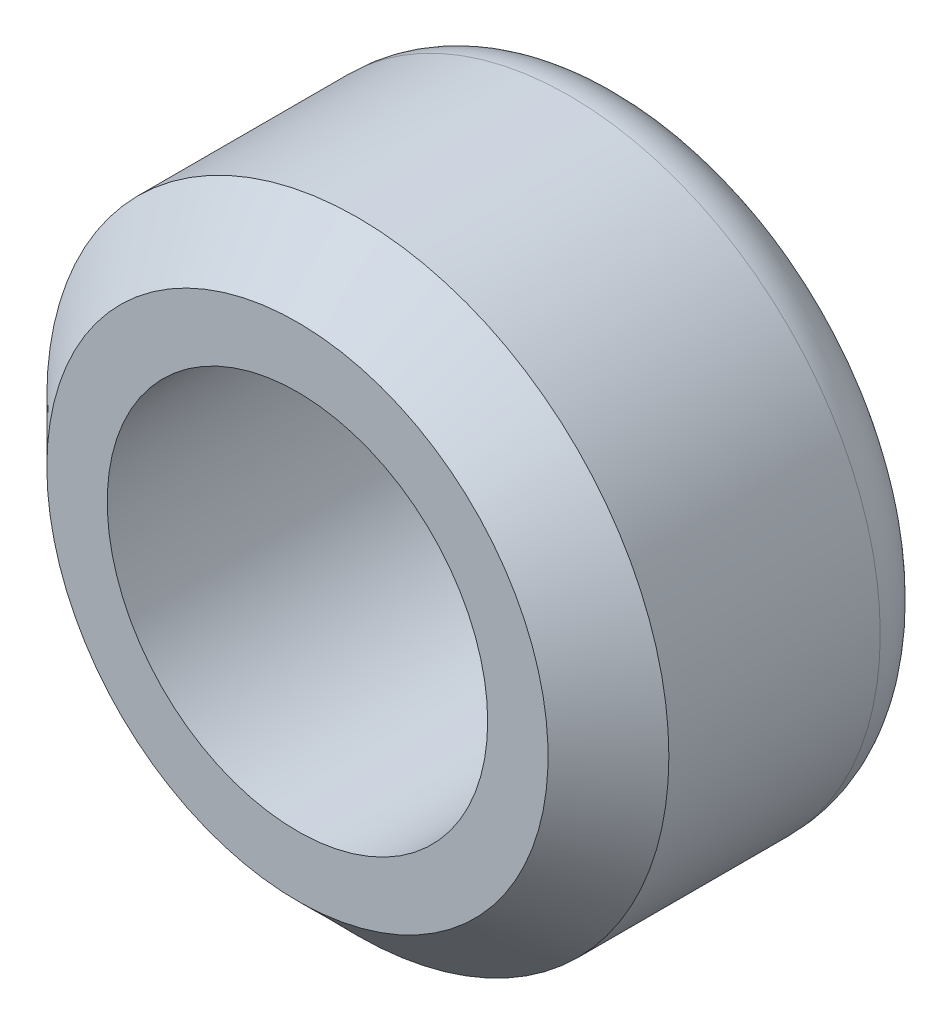
SolidWorks part; units mm, degrees
ref_plane "Front Plane" through (0, 0, 0) normal (0, 0, 1) x (1, 0, 0)
ref_plane "Top Plane" through (0, 0, 0) normal (0, 1, 0) x (1, 0, 0)
ref_plane "Right Plane" through (0, 0, 0) normal (1, 0, 0) x (0, 0, -1)
sketch "Sketch1" plane through (0, 0, 0) normal (0, 1, 0) x (1, 0, 0)
  line L0 (-3, 5.3) -> (3, 5.3) construction
  line L1 (-3, 5.3) -> (3, 5.3) construction
  line L2 (2.8, 5.5) -> (-2.8, 5.5) construction
  line L3 (2.8, 5.5) -> (-2.8, 5.5) construction
  line L4 (3, 3) -> (-3, 3) construction
  line L5 (3, 3) -> (-3, 3) construction
  line L6 (-3, 5.3) -> (-3, 3) construction
  line L7 (0, 0) -> (0, 7.0688) construction
  line L8 (-5.15, 5.5) -> (-3.15, 5.5)
  line L9 (-5.15, 5.5) -> (-5.15, 0)
  line L10 (-5.15, 0) -> (-3.15, 0)
  line L11 (-3.15, 5.5) -> (-3.15, 0)
  point P14 (-3.1508, 0)
  dimension "D1" = 2
  dimension "D2" = 0.15
revolve "Revolve1" add sketch "Sketch1" angle 360 about L7
chamfer "Chamfer1" distance 1 angle 45 1 edges at (5.15, 0, 0)
fillet "Fillet1" radius 1 1 edges at (5.15, 0, -5.5)
